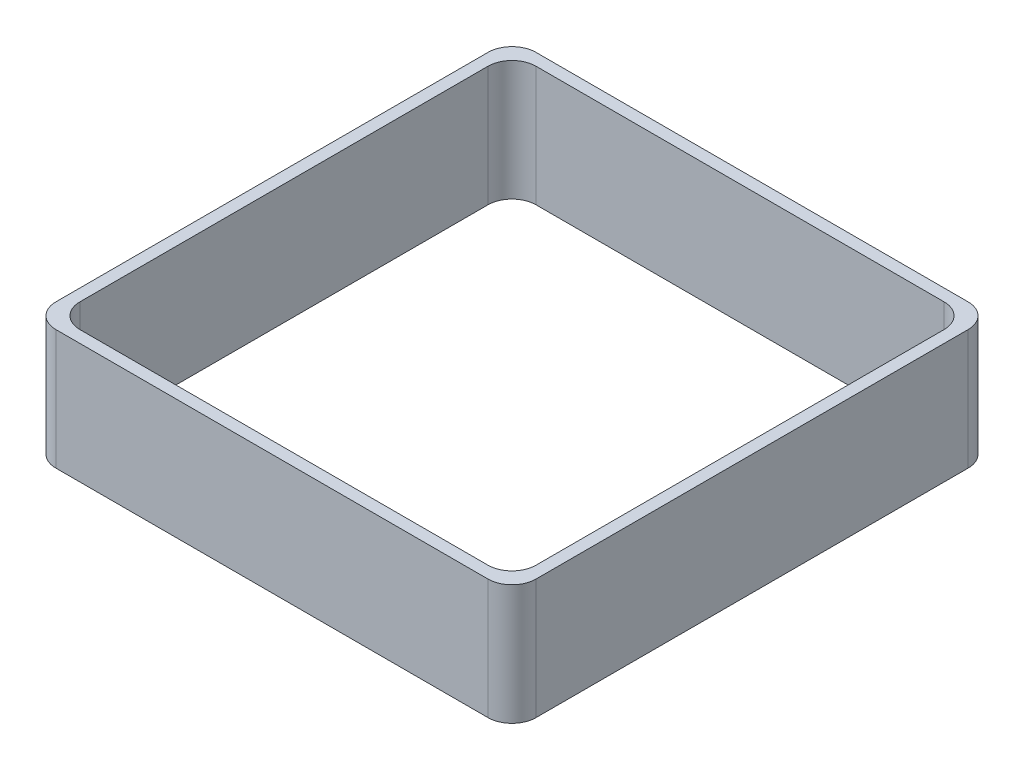
SolidWorks part; units mm, degrees
ref_plane "Front" through (0, 0, 0) normal (0, 0, 1) x (1, 0, 0)
ref_plane "Top" through (0, 0, 0) normal (0, 1, 0) x (1, 0, 0)
ref_plane "Right" through (0, 0, 0) normal (1, 0, 0) x (0, 0, -1)
sketch "草图1" plane through (0, 0, 0) normal (0, 1, 0) x (1, 0, 0)
  line L0 (95, 95) -> (-95, 95)
  line L1 (100, 100) -> (-100, 100)
  line L2 (100, 100) -> (100, -100)
  line L3 (100, -100) -> (-100, -100)
  line L4 (-100, 100) -> (-100, -100)
  line L5 (100, 100) -> (-100, -100) construction
  line L6 (100, -100) -> (-100, 100) construction
  line L7 (-95, 95) -> (-95, -95)
  line L8 (95, -95) -> (-95, -95)
  line L9 (95, 95) -> (95, -95)
  point P0 (0, 0)
  dimension "D1" = 200
  dimension "D2" = 200
  dimension "D3" = 5
extrude "凸台-拉伸1" add sketch "草图1" along normal blind 50
fillet "圆角1" radius 10 8 edges at (-100, 25, -100) (-100, 25, 100) (100, 25, 100) (100, 25, -100) (95, 25, -95) (95, 25, 95) (-95, 25, 95) (-95, 25, -95)
